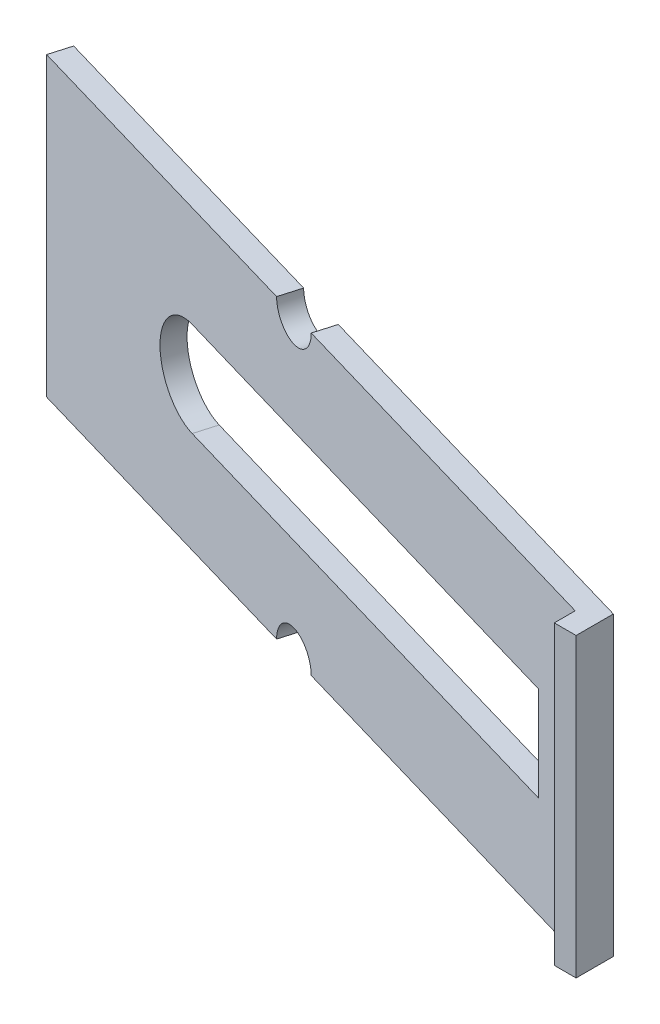
SolidWorks part; units mm, degrees
ref_plane "Front Plane" through (0, 0, 0) normal (0, 0, 1) x (1, 0, 0)
ref_plane "Top Plane" through (0, 0, 0) normal (0, 1, 0) x (1, 0, 0)
ref_plane "Right Plane" through (0, 0, 0) normal (1, 0, 0) x (0, 0, -1)
sketch "Sketch1" plane through (0, 0, 0) normal (0, 1, 0) x (1, 0, 0)
  line L0 (0, 0) -> (0, 0.4) construction
  line L1 (0, 0.4) -> (-10.3685, 3.4222) construction
  line L2 (-51.1686, 0) -> (50.4861, 0) construction
  line L3 (-0.15, 0) -> (-0.15, 0.2875)
  line L4 (-0.15, 0.2875) -> (-10.4105, 3.2781)
  line L5 (0.15, 0) -> (0.15, 0.5125)
  line L6 (0.15, 0.5125) -> (-10.3266, 3.5662)
  line L7 (-0.15, 0) -> (0.15, 0)
  line L8 (-10.4105, 3.2781) -> (-10.3266, 3.5662)
  dimension "D1" = 16.25
  dimension "D2" = 10.8
  dimension "D3" = 0.4
  dimension "D4" = 0.15
  dimension "D5" = 0.15
extrude "Boss-Extrude1" add sketch "Sketch1" along normal blind 4.08
sketch "Sketch2" plane through (0.1494, 0, -0.5127) normal (0.2798, 0, -0.96) x (-0.96, 0, -0.2798)
  line L0 (-0.0006, 2.04) -> (10.9119, 2.04) construction
  line L1 (-0.0006, 4.08) -> (-0.0006, 0) construction
  line L2 (10.9119, 4.08) -> (10.9119, 0) construction
  line L3 (0.9694, 1.39) -> (7.9694, 1.39)
  line L4 (0.9694, 2.69) -> (7.9694, 2.69)
  line L5 (0.9694, 2.69) -> (0.9694, 1.39)
  arc A0 (7.9694, 2.69) -> (7.9694, 1.39) centre (7.9694, 2.04) cw
  dimension "D1" = 1.3
  dimension "D2" = 0.97
  dimension "D3" = 7
extrude "Cut-Extrude1" cut sketch "Sketch2" against normal up to surface (0.3 mm away) up to face at (-5.2803, 2.04, -1.7828)
sketch "Sketch3" plane through (0.1494, 0, -0.5127) normal (0.2798, 0, -0.96) x (-0.96, 0, -0.2798)
  line L0 (-0.0006, 4.08) -> (10.9119, 4.08) construction
  line L1 (-0.0006, 2.04) -> (10.9119, 2.04) construction
  line L2 (-0.0006, 4.08) -> (-0.0006, 0) construction
  line L3 (10.9119, 4.08) -> (10.9119, 0) construction
  line L4 (5.5619, 4.08) -> (6.2619, 4.08)
  line L5 (5.5619, 0) -> (6.2619, 0)
  arc A0 (6.2619, 4.08) -> (5.5619, 4.08) centre (5.9119, 4.08) cw
  arc A1 (6.2619, 0) -> (5.5619, 0) centre (5.9119, 0) ccw
  dimension "D1" = 0.35
  dimension "D2" = 5
extrude "Cut-Extrude2" cut sketch "Sketch3" against normal up to surface (0.3 mm away) up to face at (-4.3814, 2.04, -1.5208)
